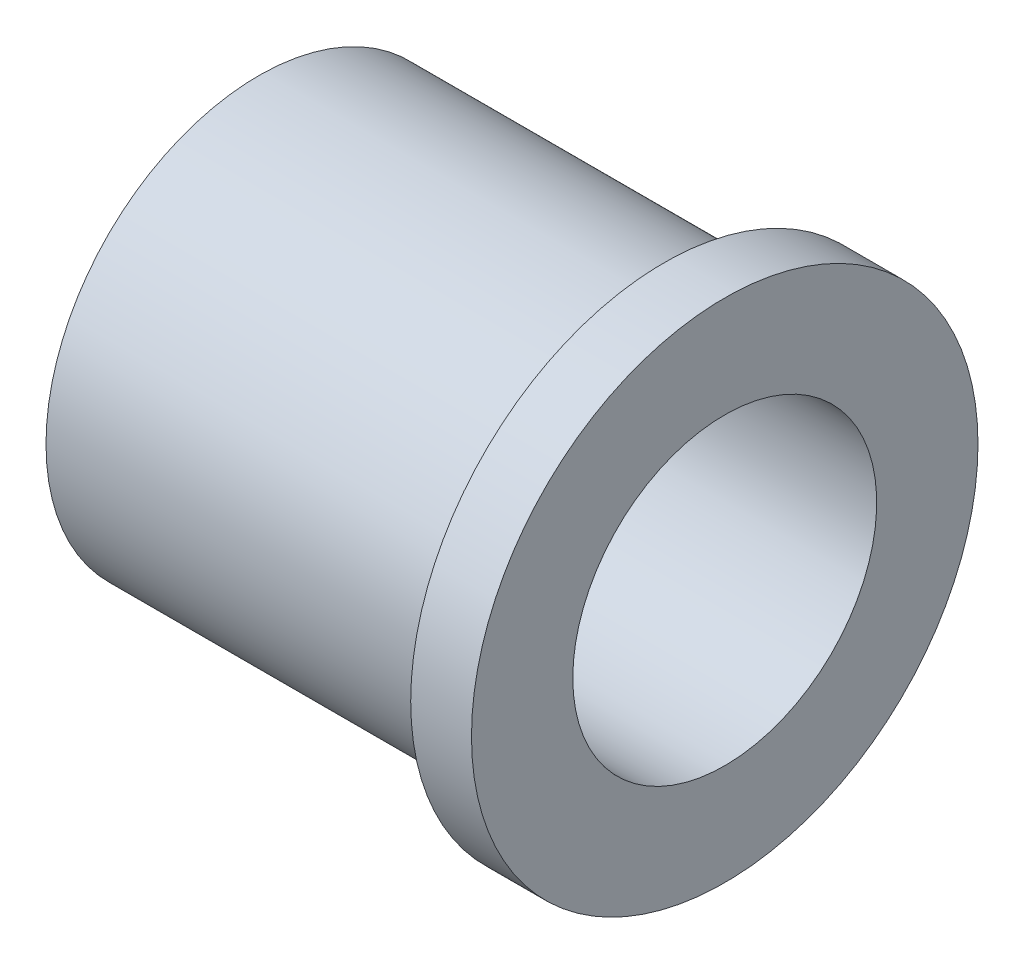
SolidWorks part; units mm, degrees
ref_plane "Front Plane" through (0, 0, 0) normal (0, 0, 1) x (1, 0, 0)
ref_plane "Top Plane" through (0, 0, 0) normal (0, 1, 0) x (1, 0, 0)
ref_plane "Right Plane" through (0, 0, 0) normal (1, 0, 0) x (0, 0, -1)
sketch "Sketch1" plane through (0, 0, 0) normal (0, 0, 1) x (1, 0, 0)
  line L0 (0, 0) -> (22.0808, 0) construction
  line L1 (0, 5.25) -> (0, 3.75)
  line L2 (0, 3.75) -> (11.5, 3.75)
  line L3 (11.5, 3.75) -> (11.5, 6.25)
  line L4 (11.5, 6.25) -> (10, 6.25)
  line L5 (10, 6.25) -> (10, 5.25)
  line L6 (10, 5.25) -> (0, 5.25)
  point P3 (20.0372, 3.75)
  point P5 (2.2063, 6.5978)
  dimension "D1" = 1.5
  dimension "D2" = 7.5
  dimension "D3" = 1
  dimension "D4" = 10
revolve "Revolve1" add sketch "Sketch1" angle 360 about L0
